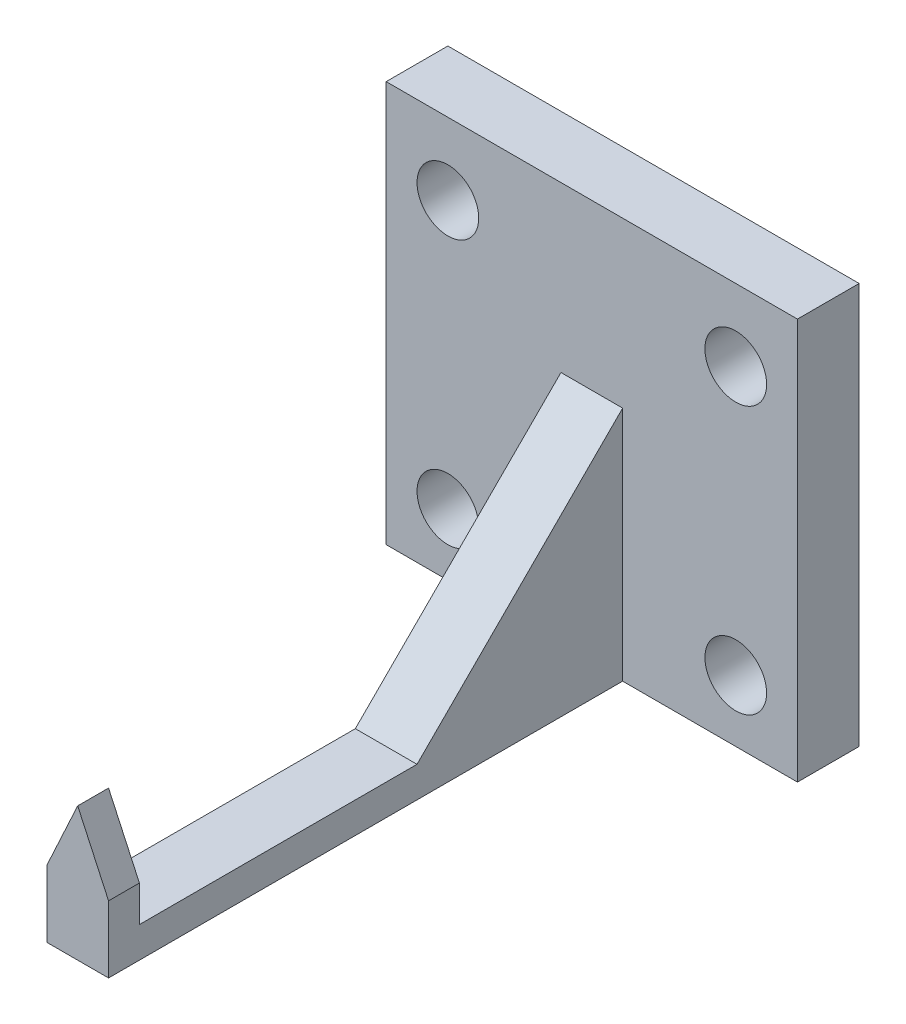
SolidWorks part; units mm, degrees
ref_plane "Спереди" through (0, 0, 0) normal (0, 0, 1) x (1, 0, 0)
ref_plane "Сверху" through (0, 0, 0) normal (0, 1, 0) x (1, 0, 0)
ref_plane "Справа" through (0, 0, 0) normal (1, 0, 0) x (0, 0, -1)
sketch "Sketch1" plane through (0, 0, 0) normal (0, 1, 0) x (1, 0, 0)
  line L0 (3, 25) -> (11.5, 25)
  line L1 (0, 0) -> (3, 0)
  line L2 (0, 0) -> (0, 25)
  line L3 (-8.5, 28) -> (11.5, 28)
  line L4 (3, 0) -> (3, 25)
  line L6 (-8.5, 28) -> (-8.5, 25)
  line L7 (-8.5, 25) -> (0, 25)
  line L8 (11.5, 28) -> (11.5, 25)
  dimension "D1" = 3
  dimension "D2" = 3
  dimension "D3" = 20
  dimension "D4" = 28
extrude "Boss-Extrude1" add sketch "Sketch1" along normal blind 1.5
sketch "Sketch2" plane through (0, 1.5, 0) normal (0, 1, 0) x (1, 0, 0)
  line L0 (3, 0) -> (3, 25) construction
  line L1 (0, 0) -> (3, 0)
  line L2 (0, 0) -> (0, 1.5)
  line L3 (0, 1.5) -> (3, 1.5)
  line L4 (3, 0) -> (3, 1.5)
  dimension "D1" = 1.5
extrude "Boss-Extrude2" add sketch "Sketch2" along normal blind 5
sketch "Sketch3" plane through (0, 1.5, 0) normal (0, 1, 0) x (1, 0, 0)
  line L2 (-8.5, 28) -> (11.5, 28)
  line L3 (-8.5, 28) -> (-8.5, 25)
  line L4 (-8.5, 25) -> (11.5, 25)
  line L5 (11.5, 28) -> (11.5, 25)
extrude "Boss-Extrude3" add sketch "Sketch3" along normal blind 18
sketch "Sketch4" plane through (0, 0, 0) normal (0, 0, 1) x (1, 0, 0)
  line L0 (1.5, 6.5) -> (0, 3.25)
  line L1 (0, 6.5) -> (3, 6.5) construction
  line L2 (0, 6.5) -> (0, 0) construction
  line L3 (1.5, 6.5) -> (3, 3.25)
  line L4 (3, 6.5) -> (3, 0) construction
  line L5 (3, 3.25) -> (5.7094, 3.25)
  line L6 (5.7094, 3.25) -> (5.303, 8.6765)
  line L7 (5.303, 8.6765) -> (-2.0262, 8.1275)
  line L8 (-2.0262, 8.1275) -> (-1.6609, 3.25)
  line L9 (-1.6609, 3.25) -> (0, 3.25)
extrude "Cut-Extrude1" cut sketch "Sketch4" against normal blind 10
sketch "Sketch5" plane through (0, 0, -25) normal (0, 0, 1) x (1, 0, 0)
  line L0 (-8.5, 19.5) -> (-8.5, 0) construction
  circle A0 centre (-5.5, 3) radius 1.5
  circle A1 centre (8.5, 3) radius 1.5
  circle A2 centre (8.5, 16) radius 1.5
  circle A3 centre (-5.5, 16) radius 1.5
  dimension "D1" = 3
  dimension "D2" = 3
  dimension "D3" = 3
  dimension "D4" = 2
  dimension "D5" = 2
extrude "Cut-Extrude4" cut sketch "Sketch5" against normal blind 10
sketch "Sketch6" plane through (0, 0, 0) normal (-1, 0, 0) x (0, 0, 1)
  line L0 (-25, 1.5) -> (-25, 11.5)
  line L1 (-25, 19.5) -> (-25, 0) construction
  line L2 (-25, 1.5) -> (-15, 1.5)
  line L3 (-25, 1.5) -> (-1.5, 1.5) construction
  line L4 (-25, 11.5) -> (-15, 1.5)
  dimension "D1" = 10
  dimension "D2" = 10
extrude "Boss-Extrude4" add sketch "Sketch6" against normal blind 3
